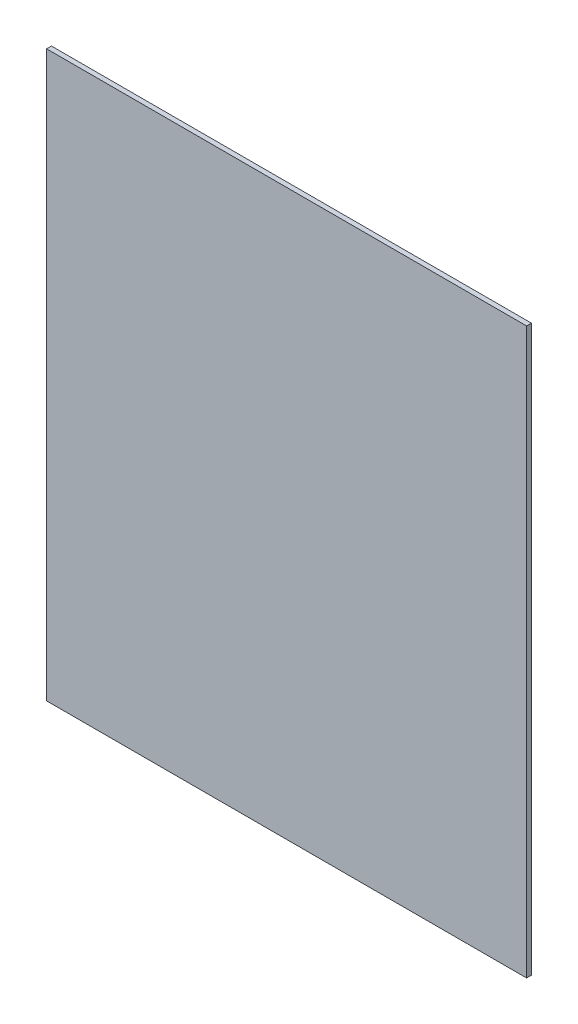
SolidWorks part; units mm, degrees
material "ABS"
ref_plane "Front Plane" through (0, 0, 0) normal (0, 0, 1) x (1, 0, 0)
ref_plane "Top Plane" through (0, 0, 0) normal (0, 1, 0) x (1, 0, 0)
ref_plane "Right Plane" through (0, 0, 0) normal (1, 0, 0) x (0, 0, -1)
sketch "Sketch1" plane through (0, 0, 0) normal (0, 0, 1) x (1, 0, 0)
  line L1 (0, 0) -> (59.5, 0)
  line L2 (0, 0) -> (0, -70)
  line L3 (0, -70) -> (59.5, -70)
  line L4 (59.5, 0) -> (59.5, -70)
  dimension "D1" = 59.5
  dimension "D2" = 70
extrude "Boss-Extrude1" add sketch "Sketch1" along normal blind 0.6
sketch "Sketch2" plane through (0, 0, 0) normal (0, 0, -1) x (-1, 0, 0)
  line L0 (-29.3603, -22.9065) -> (-29.3603, -42.2587) construction
  spline S0 degree 3 poles (-29.3603, -22.9065) (-27.4522, -19.0677) (-12.9459, -12.8706) (-9.2995, -33.44) (-29.3603, -42.2587) knots 0 0 0 0 0.41261 1 1 1 1
  spline S1 degree 3 poles (-29.3603, -22.9065) (-31.2684, -19.0677) (-45.7747, -12.8706) (-49.4211, -33.44) (-29.3603, -42.2587) knots 0 0 0 0 0.41261 1 1 1 1
extrude "Boss-Extrude2" add sketch "Sketch2" along normal blind 0.4
sketch "Sketch3" plane through (0, 0, 0) normal (0, 0, -1) x (-1, 0, 0)
  text T0 " DLRR" font "Arial" height in points 22
extrude "Boss-Extrude3" add sketch "Sketch3" along normal blind 0.4
